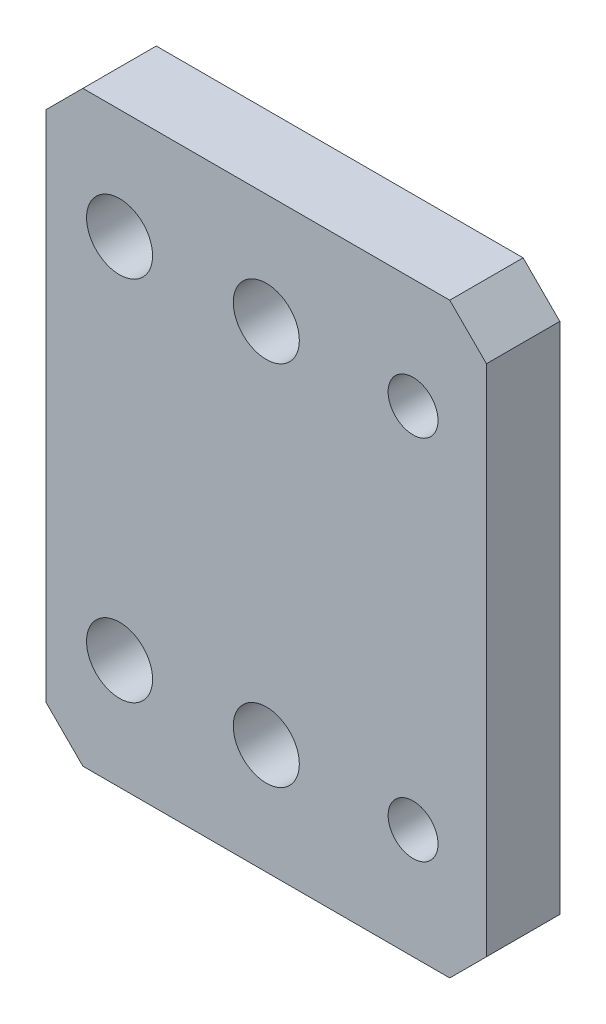
SolidWorks part; units mm, degrees
material "Q235"
ref_plane "前视基准面" through (0, 0, 0) normal (0, 0, 1) x (1, 0, 0)
ref_plane "上视基准面" through (0, 0, 0) normal (0, 1, 0) x (1, 0, 0)
ref_plane "右视基准面" through (0, 0, 0) normal (1, 0, 0) x (0, 0, -1)
sketch "草图1" plane through (0, 0, 0) normal (0, 0, 1) x (1, 0, 0)
  line L0 (0, 0) -> (-64.0846, 0) construction
  line L1 (-40, 40) -> (20, 40)
  line L2 (-40, 40) -> (-40, -40)
  line L3 (-40, -40) -> (20, -40)
  line L4 (20, 40) -> (20, -40)
  line L5 (-40, 40) -> (20, -40) construction
  line L6 (-40, -40) -> (20, 40) construction
  point P0 (-10, 0)
  dimension "D1" = 60
  dimension "D2" = 80
  dimension "D3" = 10
extrude "凸台-拉伸1" add sketch "草图1" along normal blind 10
chamfer "倒角1" distance 5 angle 45 4 edges at (20, 40, 5) (-40, 40, 5) (20, -40, 5) (-40, -40, 5)
hole_wizard "Ø9.0 (9) 直径孔1" positions "草图4" profile "草图3" hole size "Ø9.0" standard "ISO"
sketch "草图4" plane through (0, 0, 10) normal (0, 0, 1) x (1, 0, 0)
  line L1 (10, -25) -> (-30, -25) construction
  line L2 (10, -25) -> (10, 25) construction
  line L3 (10, 25) -> (-30, 25) construction
  line L4 (-30, -25) -> (-30, 25) construction
  line L5 (20, -35) -> (20, 35) construction
  line L6 (-40, 0) -> (20, 0) construction
  line L7 (-40, 35) -> (-40, -35) construction
  point P203 (-30, 25)
  point P205 (-30, -25)
  point P215 (-10, -25)
  point P217 (-10, 25)
  dimension "D1" = 40
  dimension "D2" = 10
  dimension "D3" = 50
  dimension "D4" = 25
sketch "草图3" plane through (-30, 25, 10) normal (1, 0, 0) x (0, -1, 0)
  line L0 (0, 0) -> (0, 37.2039)
  line L1 (0, 37.2039) -> (4.5, 34.5)
  line L2 (4.5, 34.5) -> (4.5, 0)
  line L5 (4.5, 0) -> (0, 0)
  line L10 (0, 37.2039) -> (-4.5, 34.5) construction
  line L11 (0, -6.35) -> (0, 107.95) construction
  dimension "孔直径" = 9
  dimension "孔深度" = 34.5
  dimension "导头角度" = 118
hole_wizard "M8 螺纹孔3" positions "草图8" profile "草图7" tap size "M8" standard "GB"
sketch "草图8" plane through (0, 0, 10) normal (0, 0, 1) x (1, 0, 0)
  line L3 (-10, -25) -> (10, -25) construction
  line L4 (-10, -25) -> (-10, 25) construction
  line L5 (-10, 25) -> (10, 25) construction
  line L6 (10, -25) -> (10, 25) construction
  point P0 (10, -25)
  point P1 (10, 25)
  dimension "D1" = 20
sketch "草图7" plane through (10, -25, 10) normal (1, 0, 0) x (0, -1, 0)
  line L0 (0, 0) -> (0, 24.2929)
  line L1 (0, 24.2929) -> (3.4, 22.25)
  line L2 (3.4, 22.25) -> (3.4, 0)
  line L5 (3.4, 0) -> (0, 0)
  line L10 (0, 24.2929) -> (-3.4, 22.25) construction
  line L11 (0, -6.35) -> (0, 107.95) construction
  dimension "螺纹孔钻头直径" = 6.8
  dimension "螺纹孔钻头深度" = 22.25
  dimension "导头角度" = 118
cosmetic thread "孔螺蚊线5" parameters "D1"=10, "D2"=8
cosmetic thread "孔螺蚊线6" parameters "D1"=10, "D2"=8
